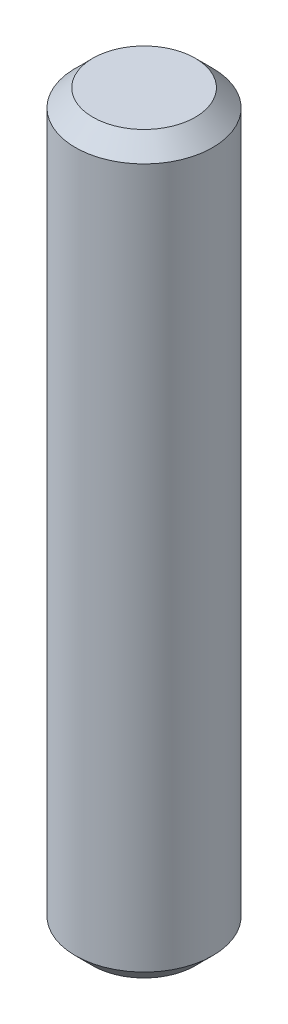
SolidWorks part; units mm, degrees
ref_plane "Front Plane" through (0, 0, 0) normal (0, 0, 1) x (1, 0, 0)
ref_plane "Top Plane" through (0, 0, 0) normal (0, 1, 0) x (1, 0, 0)
ref_plane "Right Plane" through (0, 0, 0) normal (1, 0, 0) x (0, 0, -1)
sketch "Sketch1" plane through (0, 0, 0) normal (0, 1, 0) x (1, 0, 0)
  circle A0 centre (0, 0) radius 3.925
  dimension "D1" = 7.85
extrude "Boss-Extrude1" add sketch "Sketch1" along normal blind 42
chamfer "Chamfer1" distance 1 angle 45 2 edges at (0, 0, 3.925) (0, 42, 3.925)
